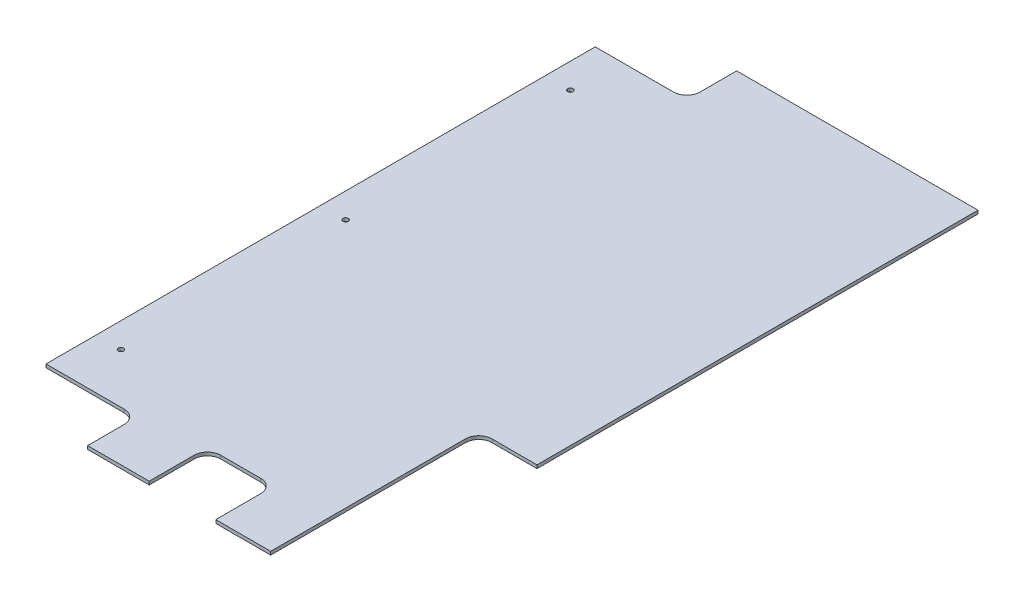
SolidWorks part; units mm, degrees
ref_plane "Alzado" through (0, 0, 0) normal (0, 0, 1) x (1, 0, 0)
ref_plane "Planta" through (0, 0, 0) normal (0, 1, 0) x (1, 0, 0)
ref_plane "Vista lateral" through (0, 0, 0) normal (1, 0, 0) x (0, 0, -1)
sketch "Croquis1" plane through (0, 0, 0) normal (0, 1, 0) x (1, 0, 0)
  line L1 (0, 0) -> (200, 0)
  line L2 (0, 0) -> (0, 390)
  line L3 (0, 390) -> (200, 390)
  line L4 (200, 0) -> (200, 390)
  dimension "D1" = 390
  dimension "D2" = 200
extrude "Saliente-Extruir1" add sketch "Croquis1" along normal blind 2
sketch "Croquis3" plane through (0, 2, 0) normal (0, 1, 0) x (1, 0, 0)
  line L0 (100, 390) -> (100, 0) construction
  line L5 (200, 390) -> (0, 390) construction
  line L6 (0, 0) -> (200, 0) construction
  line L19 (0, 195) -> (200, 195) construction
  line L20 (0, 390) -> (55, 390)
  line L21 (0, 390) -> (0, 360)
  line L22 (0, 360) -> (55, 360)
  line L23 (55, 390) -> (55, 360)
  line L24 (0, 390) -> (0, 0) construction
  line L25 (200, 0) -> (200, 390) construction
  line L26 (55, 0) -> (55, 30)
  line L27 (0, 30) -> (55, 30)
  line L28 (0, 0) -> (0, 30)
  line L29 (0, 0) -> (55, 0)
  dimension "D1" = 30
  dimension "D2" = 55
extrude "Cortar-Extruir1" cut sketch "Croquis3" against normal up to surface (2 mm away) up to face at (100, 0, -195)
sketch "Croquis5" plane through (0, 2, 0) normal (0, 1, 0) x (1, 0, 0)
  line L0 (55, 0) -> (200, 0) construction
  line L1 (92, 0) -> (132, 0)
  line L2 (92, 0) -> (92, 35)
  line L3 (92, 35) -> (132, 35)
  line L4 (132, 0) -> (132, 35)
  line L5 (55, 0) -> (55, 30) construction
  dimension "D1" = 40
  dimension "D2" = 37
  dimension "D3" = 35
extrude "Cortar-Extruir3" cut sketch "Croquis5" against normal up to surface (2 mm away) up to face at (77.5, 0, -195)
sketch "Croquis6" plane through (0, 2, 0) normal (0, 1, 0) x (1, 0, 0)
  line L1 (200, 0) -> (165, 0)
  line L2 (200, 0) -> (200, 125)
  line L3 (200, 125) -> (165, 125)
  line L4 (165, 0) -> (165, 125)
  dimension "D1" = 125
  dimension "30" = 35
extrude "Cortar-Extruir4" cut sketch "Croquis6" against normal up to surface (2 mm away) up to face at (89, 0, -135.8333)
sketch "Croquis7" plane through (0, 2, 0) normal (0, 1, 0) x (1, 0, 0)
  line L0 (15.05, 360) -> (15.05, 30) construction
  line L1 (0, 360) -> (55, 360) construction
  line L2 (55, 30) -> (0, 30) construction
  line L3 (0, 360) -> (0, 30) construction
  line L4 (0, 195) -> (200, 195) construction
  line L5 (200, 125) -> (200, 390) construction
  circle A0 centre (15.05, 330) radius 1.6
  circle A1 centre (15.05, 195) radius 1.6
  circle A2 centre (15.05, 60) radius 1.6
  dimension "D2" = 3.2
  dimension "D1" = 15.05
  dimension "D3" = 30
  dimension "D4" = 30
extrude "Cortar-Extruir5" cut sketch "Croquis7" against normal up to surface (2 mm away) up to face at (99.8571, 0, -134.2857)
fillet "Redondeo1" radius 8 5 edges at (165, 1, -125) (55, 1, -30) (92, 1, -35) (132, 1, -35) (55, 1, -360)
